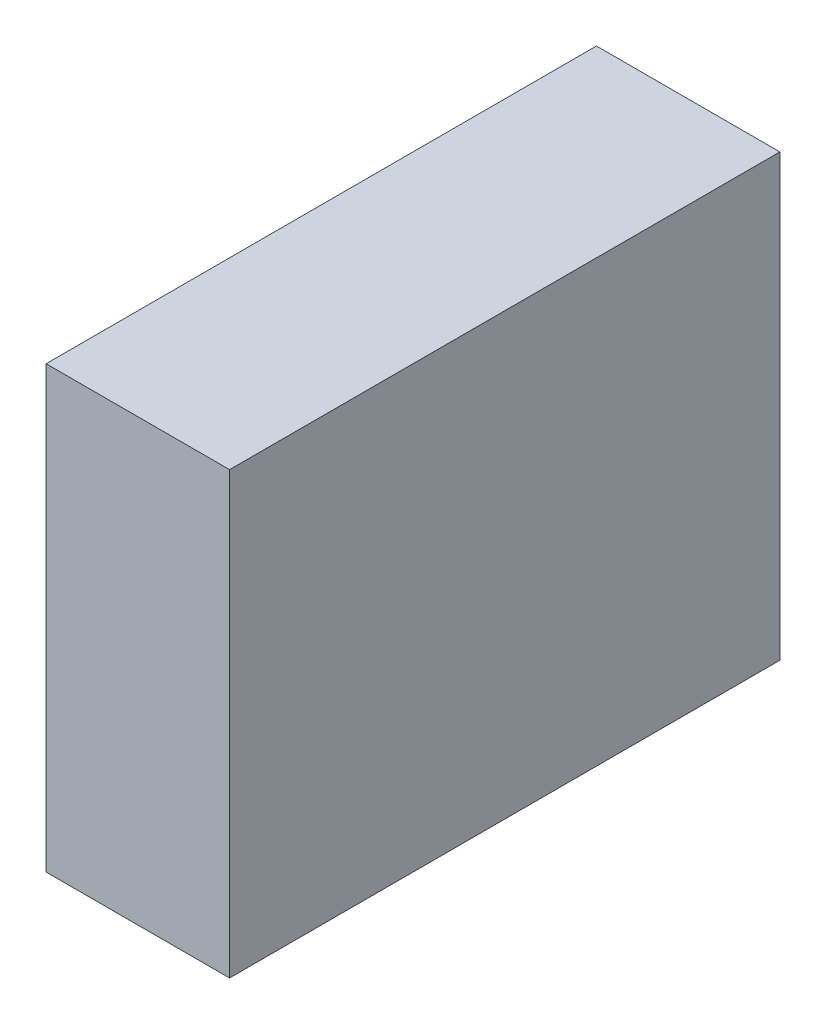
SolidWorks part; units mm, degrees
ref_plane "Front Plane" through (0, 0, 0) normal (0, 0, 1) x (1, 0, 0)
ref_plane "Top Plane" through (0, 0, 0) normal (0, 1, 0) x (1, 0, 0)
ref_plane "Right Plane" through (0, 0, 0) normal (1, 0, 0) x (0, 0, -1)
sketch "Sketch1" plane through (0, 0, 0) normal (0, 1, 0) x (1, 0, 0)
  line L1 (22.3649, 82.6014) -> (27.3649, 82.6014)
  line L2 (22.3649, 82.6014) -> (22.3649, 67.6014)
  line L3 (22.3649, 67.6014) -> (27.3649, 67.6014)
  line L4 (27.3649, 82.6014) -> (27.3649, 67.6014)
  dimension "D1" = 15
  dimension "D2" = 5
extrude "Boss-Extrude1" add sketch "Sketch1" along normal blind 12
